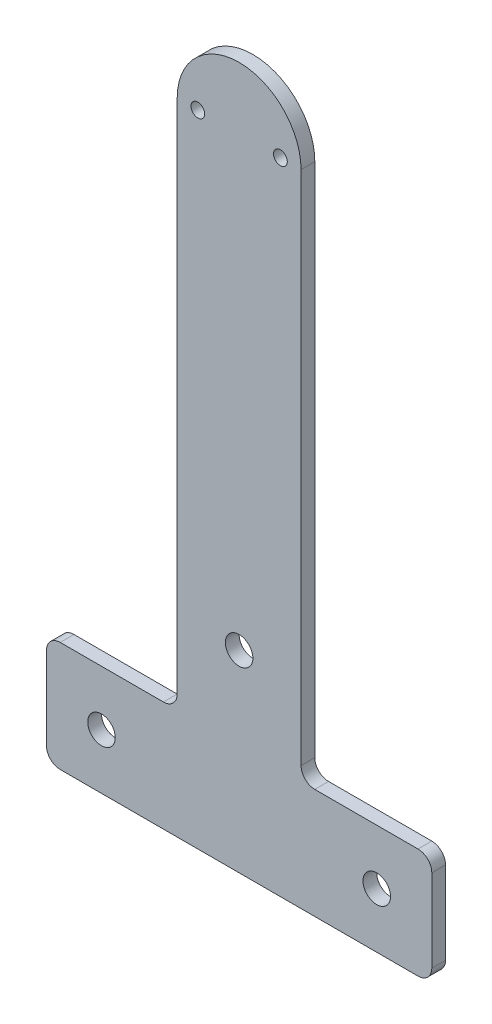
SolidWorks part; units mm, degrees
ref_plane "前视基准面" through (0, 0, 0) normal (0, 0, 1) x (1, 0, 0)
ref_plane "上视基准面" through (0, 0, 0) normal (0, 1, 0) x (1, 0, 0)
ref_plane "右视基准面" through (0, 0, 0) normal (1, 0, 0) x (0, 0, -1)
sketch "草图1" plane through (0, 0, 0) normal (0, 0, 1) x (1, 0, 0)
  line L2 (-13.3404, 27.5655) -> (-13.3404, 112.5655) construction
  line L3 (-13.3404, 112.5655) -> (-7.3404, 112.5655) construction
  line L4 (-22.3404, 112.5655) -> (-22.3404, 35.5655)
  line L6 (14.6596, 19.5655) -> (14.6596, 35.5655)
  line L9 (-41.3404, 19.5655) -> (-41.3404, 35.5655)
  line L11 (-41.3404, 35.5655) -> (-22.3404, 35.5655)
  line L13 (-4.3404, 112.5655) -> (-4.3404, 35.5655)
  line L14 (-33.3404, 27.5655) -> (-13.3404, 27.5655) construction
  line L15 (-13.3404, 27.5655) -> (6.6596, 27.5655) construction
  line L16 (-4.3404, 35.5655) -> (14.6596, 35.5655)
  line L17 (-41.3404, 19.5655) -> (14.6596, 19.5655)
  circle A4 centre (-33.3404, 27.5655) radius 2
  circle A5 centre (6.6596, 27.5655) radius 2
  circle A7 centre (-7.3404, 112.5655) radius 1
  circle A8 centre (-19.3404, 112.5655) radius 1
  circle A9 centre (-13.3404, 112.5655) radius 1.1 construction
  circle A10 centre (-13.3404, 112.5655) radius 9 construction
  arc A11 (-22.3404, 112.5655) -> (-4.3404, 112.5655) centre (-13.3404, 112.5655) cw
  circle A12 centre (-13.3404, 47.5655) radius 2
  dimension "D5" = 18
  dimension "D6" = 2
  dimension "D7" = 4
  dimension "D8" = 65
  dimension "D2" = 20
  dimension "D3" = 8
  dimension "D4" = 8
  dimension "D9" = 8
  dimension "D10" = 20
  dimension "D11" = 20
  dimension "D12" = 8
extrude "凸台-拉伸1" add sketch "草图1" along normal blind 2
fillet "圆角1" radius 2 6 edges at (-4.3404, 35.5655, 1) (14.6596, 35.5655, 1) (14.6596, 19.5655, 1) (-41.3404, 19.5655, 1) (-41.3404, 35.5655, 1) (-22.3404, 35.5655, 1)
